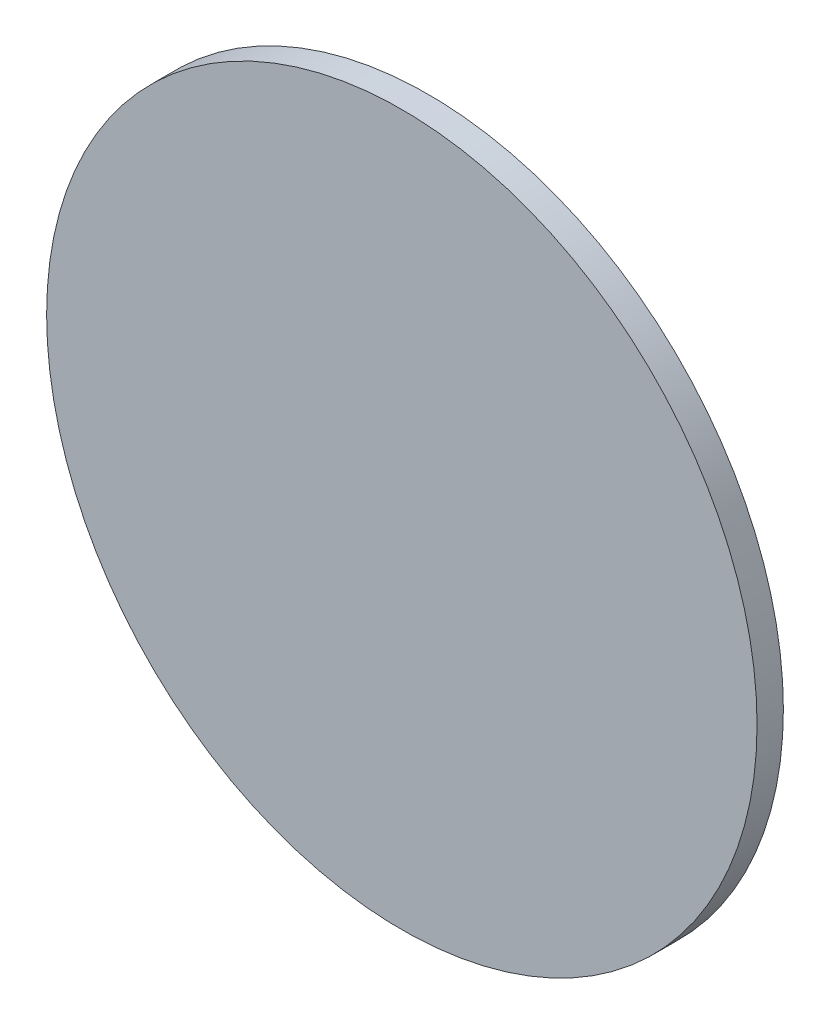
SolidWorks part; units mm, degrees
material "丙烯酸(中高冲击)"
ref_plane "Front Plane" through (0, 0, 0) normal (0, 0, 1) x (1, 0, 0)
ref_plane "Top Plane" through (0, 0, 0) normal (0, 1, 0) x (1, 0, 0)
ref_plane "Right Plane" through (0, 0, 0) normal (1, 0, 0) x (0, 0, -1)
sketch "草图1" plane through (0, 0, 0) normal (0, 0, 1) x (1, 0, 0)
  circle A0 centre (0, 0) radius 27
extrude "凸台-拉伸1" add sketch "草图1" along normal blind 2
